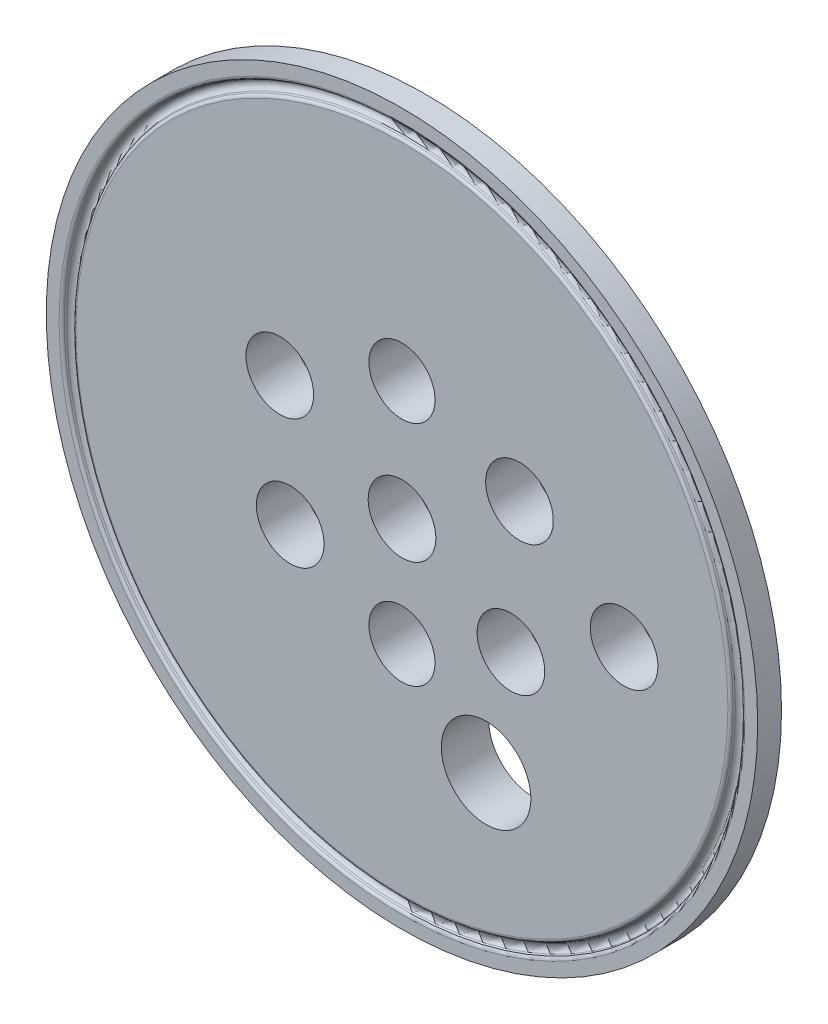
SolidWorks part; units mm, degrees
other "Markup1"
sketch "Sketch3"
ref_plane "Front Plane" through (0, 0, 0) normal (0, 0, 1) x (1, 0, 0)
ref_plane "Top Plane" through (0, 0, 0) normal (0, 1, 0) x (1, 0, 0)
ref_plane "Right Plane" through (0, 0, 0) normal (1, 0, 0) x (0, 0, -1)
sketch "Sketch1" plane through (0, 0, 0) normal (1, 0, 0) x (0, 0, -1)
  line L0 (0, 0) -> (11.0998, 0) construction
  line L1 (0, 0) -> (0, 76.4446)
  line L2 (0, 83.439) -> (5.588, 83.439)
  line L3 (5.588, 83.439) -> (11.0998, 68.2955)
  line L4 (11.0998, 68.2955) -> (11.0998, 0)
  line L5 (0, 80.4258) -> (0, 83.439)
  line L6 (0.4797, 79.701) -> (0.8729, 79.5341)
  line L7 (0.4797, 77.1694) -> (0.8729, 77.3363)
  line L8 (0, 79.9046) -> (0, 76.9658) construction
  line L9 (0, 78.4352) -> (0.4064, 78.4352) construction
  line L10 (0, 0) -> (11.0998, 0)
  arc A0 (0.8729, 77.3363) -> (0.8729, 79.5341) centre (0.4064, 78.4352) ccw
  arc A2 (0, 76.4446) -> (0.4797, 77.1694) centre (0.7874, 76.4446) cw
  arc A3 (0, 80.4258) -> (0.4797, 79.701) centre (0.7874, 80.4258) ccw
  dimension "K" = 1.1938
  dimension "L" = 0.7874
  dimension "I" = 20
  dimension "C" = 136.5909
  dimension "F" = 5.588
  dimension "H" = 0.4064
  dimension "B" = 156.8704
  dimension "A" = 166.878
  dimension "M" = 46
  dimension "N" = 23
  dimension "Length" = 11.0998
revolve "Revolve1" add sketch "Sketch1" angle 360 about L0
sketch "Sketch2" plane through (0, 0, -11.0998) normal (0, 0, -1) x (-1, 0, 0)
  circle A0 centre (0, 0) radius 7.9375
  circle A1 centre (0, 0) radius 13.716 construction
  circle A4 centre (0, 27.9766) radius 7.75
  circle A6 centre (-25.5524, -14.3084) radius 7.9375
  circle A7 centre (-25.5524, -14.3084) radius 13.716 construction
  circle A8 centre (-52.092, 0) radius 7.9375
  circle A9 centre (-52.092, 0) radius 13.716 construction
  circle A10 centre (26.2227, -14.3084) radius 7.9375
  circle A11 centre (26.2227, -14.3084) radius 13.716 construction
  circle A12 centre (-27.5561, 17.3336) radius 7.9375
  circle A13 centre (-27.5561, 17.3336) radius 13.716 construction
  circle A14 centre (28.6553, 14.7872) radius 7.9375
  circle A15 centre (28.6553, 14.7872) radius 13.716 construction
  circle A16 centre (0, 27.9766) radius 10.5 construction
  circle A17 centre (0, -25.4243) radius 7.75
  circle A18 centre (0, -25.4243) radius 10.5 construction
  circle A19 centre (-19.7252, -41.7548) radius 13 construction
  circle A20 centre (-19.7252, -41.7548) radius 10.5
  dimension "D1" = 15.875
  dimension "D2" = 27.432
  dimension "D3" = 15.5
  dimension "D4" = 15.875
  dimension "D5" = 27.432
  dimension "D6" = 15.875
  dimension "D7" = 27.432
  dimension "D8" = 15.875
  dimension "D9" = 27.432
  dimension "D10" = 15.875
  dimension "D11" = 27.432
  dimension "D12" = 15.875
  dimension "D13" = 27.432
  dimension "D14" = 21
  dimension "D15" = 26
  dimension "D16" = 21
extrude "Cut-Extrude1" cut sketch "Sketch2" against normal through all
